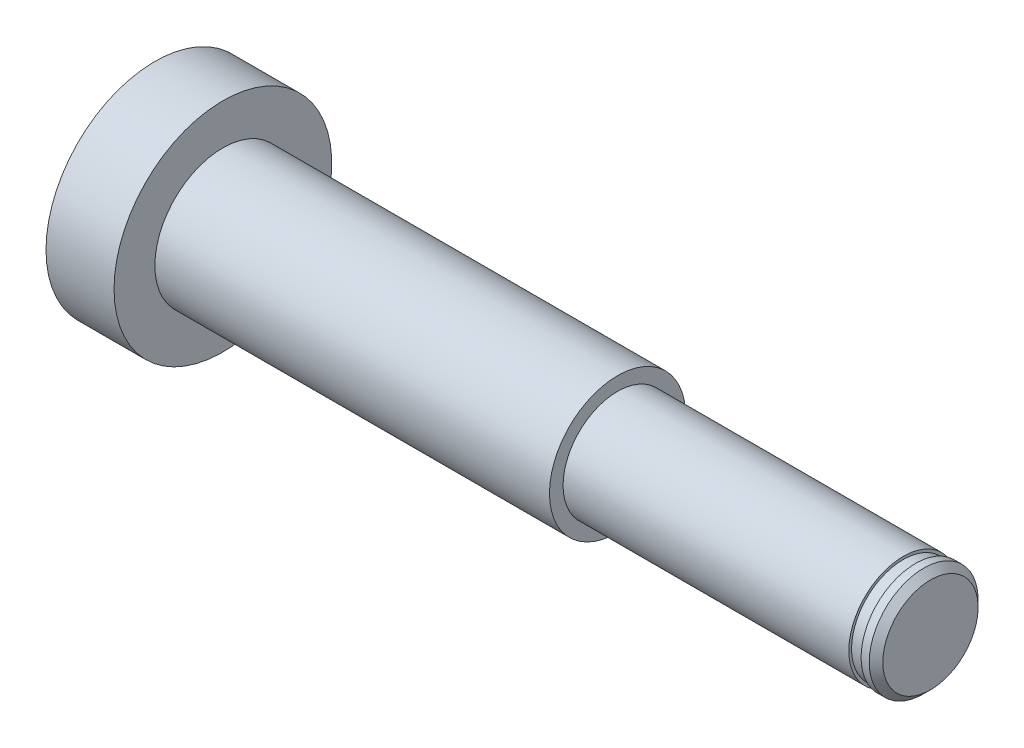
SolidWorks part; units mm, degrees
material "Простая углеродистая сталь"
ref_plane "Спереди" through (0, 0, 0) normal (0, 0, 1) x (1, 0, 0)
ref_plane "Сверху" through (0, 0, 0) normal (0, 1, 0) x (1, 0, 0)
ref_plane "Справа" through (0, 0, 0) normal (1, 0, 0) x (0, 0, -1)
sketch "Эскиз1" plane through (0, 0, 0) normal (0, 0, 1) x (1, 0, 0)
  line L0 (0, 0) -> (52, 0) construction
  line L1 (50.9, 4) -> (52, 4)
  line L2 (0, 5) -> (29, 5)
  line L3 (29, 5) -> (29, 4)
  line L4 (29, 4) -> (50, 4)
  line L5 (52, 4) -> (52, 0)
  line L6 (0, 0) -> (52, 0)
  line L8 (0, 0) -> (-5, 0)
  line L9 (0, 5) -> (0, 8)
  line L10 (0, 8) -> (-5, 8)
  line L11 (-5, 0) -> (-5, 8)
  line L12 (50.9, 4) -> (50.9, 3.8)
  line L13 (50.9, 3.8) -> (50, 3.8)
  line L14 (50, 4) -> (50, 3.8)
  dimension "D1" = 10
  dimension "D2" = 8
  dimension "D3" = 29
  dimension "D4" = 8
  dimension "D5" = 5
  dimension "D6" = 23
  dimension "D7" = 3.8
  dimension "D8" = 0.9
  dimension "D9" = 21
revolve "Повернуть1" add sketch "Эскиз1" angle 360 about L0
chamfer "Фаска1" distance 0.5 angle 45 1 edges at (52, 0, 4)
